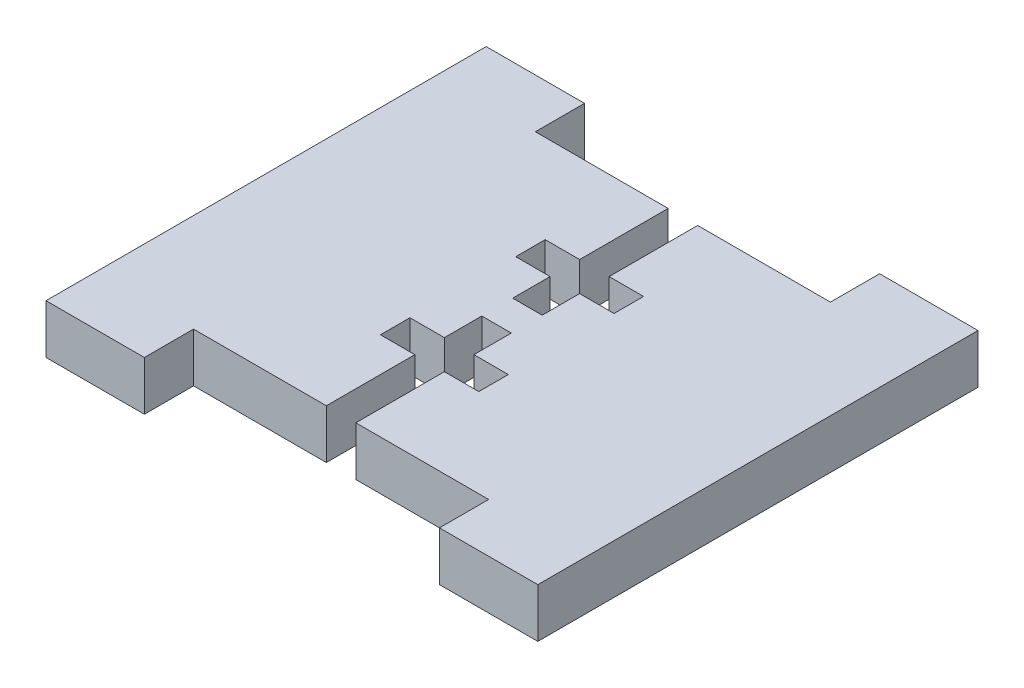
SolidWorks part; units mm, degrees
material "CA"
ref_plane "Alzado" through (0, 0, 0) normal (0, 0, 1) x (1, 0, 0)
ref_plane "Planta" through (0, 0, 0) normal (0, 1, 0) x (1, 0, 0)
ref_plane "Vista lateral" through (0, 0, 0) normal (1, 0, 0) x (0, 0, -1)
sketch "Croquis1" plane through (0, 0, 0) normal (0, 1, 0) x (1, 0, 0)
  line L0 (0, 0) -> (10, 0)
  line L1 (10, 0) -> (10, 5)
  line L2 (10, 5) -> (23.5, 5)
  line L3 (23.5, 5) -> (23.5, 14)
  line L4 (23.5, 14) -> (20, 14)
  line L5 (20, 14) -> (20, 17)
  line L6 (20, 17) -> (23.5, 17)
  line L7 (23.5, 17) -> (23.5, 20.8039)
  line L8 (23.5, 20.8039) -> (26.5, 20.8039)
  line L9 (0, 0) -> (0, 44.75)
  line L11 (23.5, 23.9461) -> (26.5, 23.9461)
  line L12 (26.5, 17) -> (26.5, 20.8039)
  line L13 (30, 17) -> (26.5, 17)
  line L14 (26.5, 5) -> (26.5, 14)
  line L15 (30, 14) -> (30, 17)
  line L16 (26.5, 14) -> (30, 14)
  line L17 (40, 5) -> (26.5, 5)
  line L18 (40, 0) -> (40, 5)
  line L19 (50, 0) -> (40, 0)
  line L20 (50, 0) -> (50, 44.75)
  line L21 (50, 44.75) -> (40, 44.75)
  line L22 (40, 44.75) -> (40, 39.75)
  line L23 (40, 39.75) -> (26.5, 39.75)
  line L24 (26.5, 30.75) -> (30, 30.75)
  line L25 (30, 30.75) -> (30, 27.75)
  line L26 (26.5, 39.75) -> (26.5, 30.75)
  line L27 (30, 27.75) -> (26.5, 27.75)
  line L28 (26.5, 27.75) -> (26.5, 23.9461)
  line L29 (23.5, 27.75) -> (23.5, 23.9461)
  line L30 (20, 27.75) -> (23.5, 27.75)
  line L31 (20, 30.75) -> (20, 27.75)
  line L32 (23.5, 30.75) -> (20, 30.75)
  line L33 (23.5, 39.75) -> (23.5, 30.75)
  line L34 (10, 39.75) -> (23.5, 39.75)
  line L35 (10, 44.75) -> (10, 39.75)
  line L36 (0, 44.75) -> (10, 44.75)
  dimension "D1" = 10
  dimension "D2" = 44.75
  dimension "D3" = 5
  dimension "D4" = 13.5
  dimension "D5" = 9
  dimension "D6" = 3.5
  dimension "D7" = 3
  dimension "D9" = 5
extrude "Saliente-Extruir1" add sketch "Croquis1" along normal blind 5
